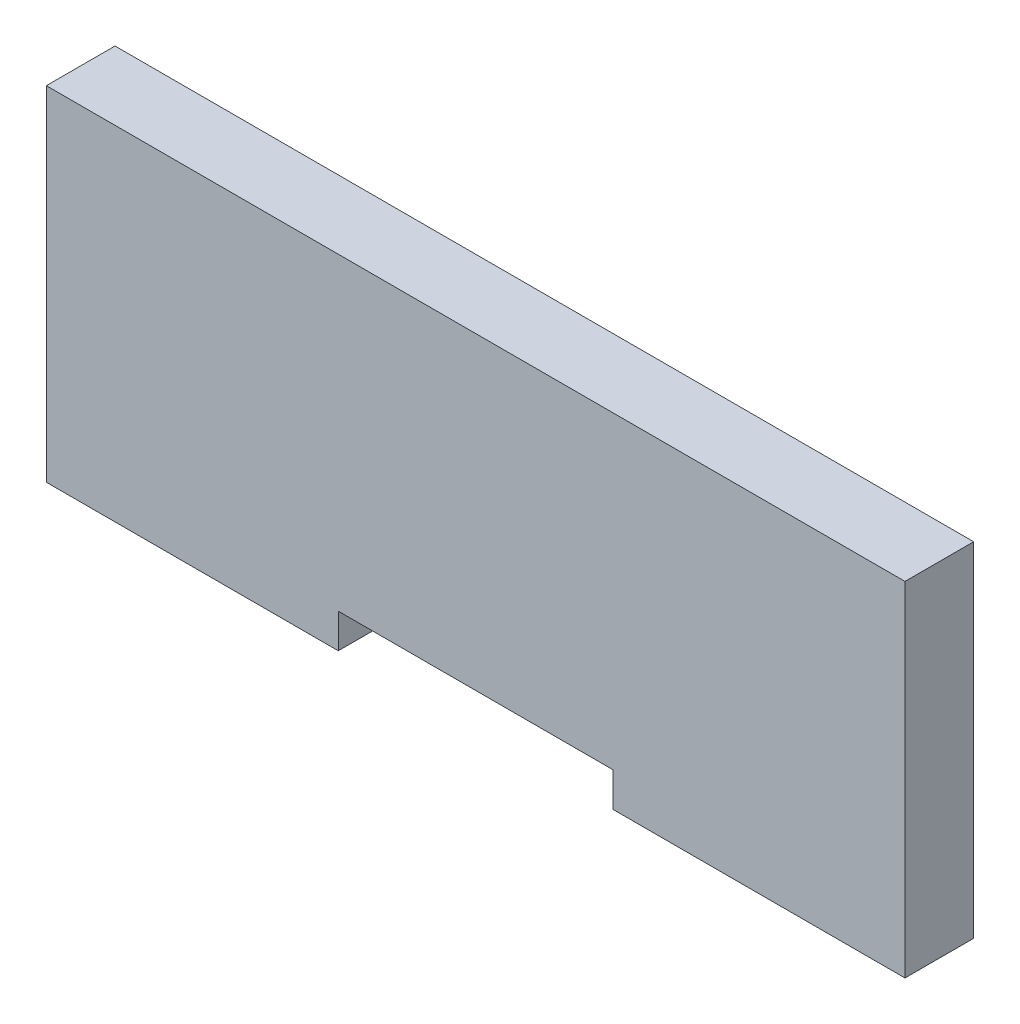
SolidWorks part; units mm, degrees
ref_plane "Front Plane" through (0, 0, 0) normal (0, 0, 1) x (1, 0, 0)
ref_plane "Top Plane" through (0, 0, 0) normal (0, 1, 0) x (1, 0, 0)
ref_plane "Right Plane" through (0, 0, 0) normal (1, 0, 0) x (0, 0, -1)
sketch "Sketch1" plane through (0, 0, 0) normal (0, 0, 1) x (1, 0, 0)
  line L0 (-40, -50) -> (-125, -50)
  line L1 (125, -50) -> (40, -50)
  line L2 (125, -50) -> (125, 50)
  line L3 (125, 50) -> (-125, 50)
  line L4 (-125, -50) -> (-125, 50)
  line L5 (125, -50) -> (-125, 50) construction
  line L6 (125, 50) -> (-125, -50) construction
  line L8 (40, -50) -> (40, -40)
  line L9 (40, -40) -> (-40, -40)
  line L10 (-40, -50) -> (-40, -40)
  point P0 (0, 0)
  point P5 (0, -50)
  dimension "D1" = 100
  dimension "D2" = 250
extrude "Boss-Extrude1" add sketch "Sketch1" along normal blind 20
